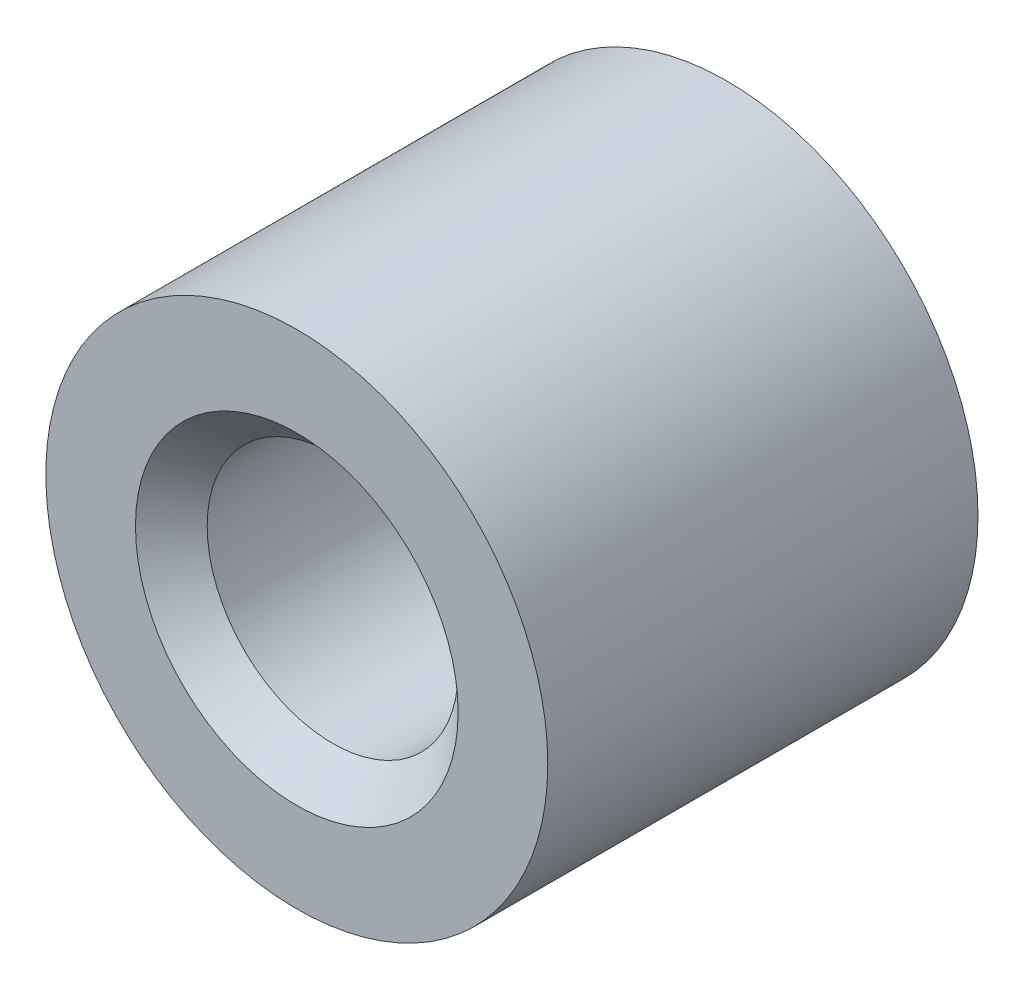
SolidWorks part; units mm, degrees
ref_plane "Спереди" through (0, 0, 0) normal (0, 0, 1) x (1, 0, 0)
ref_plane "Сверху" through (0, 0, 0) normal (0, 1, 0) x (1, 0, 0)
ref_plane "Справа" through (0, 0, 0) normal (1, 0, 0) x (0, 0, -1)
sketch "Эскиз1" plane through (0, 0, 0) normal (0, 0, 1) x (1, 0, 0)
  circle A0 centre (0, 0) radius 3.5
  dimension "D1" = 7
extrude "Бобышка-Вытянуть1" add sketch "Эскиз1" along normal blind 6
sketch "Эскиз2" plane through (0, 0, 6) normal (0, 0, 1) x (1, 0, 0)
  circle A0 centre (0, 0) radius 1.75
  dimension "D1" = 3.5
extrude "Вырез-Вытянуть1" cut sketch "Эскиз2" against normal blind 6
chamfer "Фаска1" distance 0.5 angle 45 1 edges at (1.75, 0, 6)
